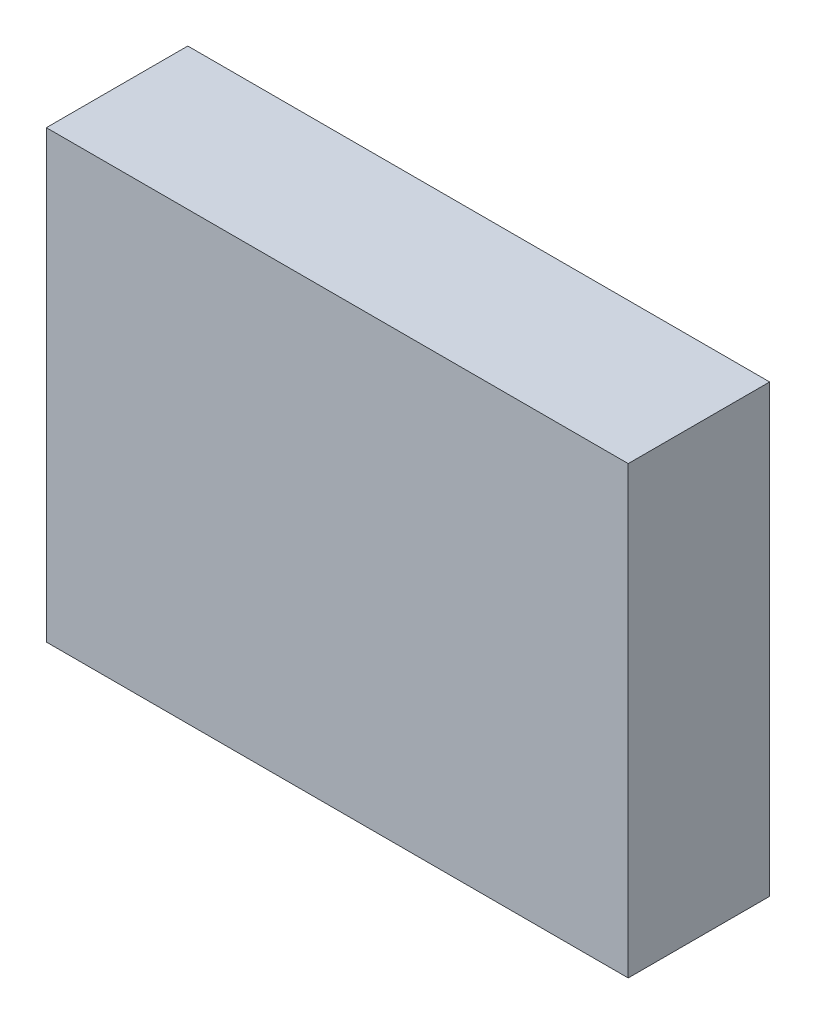
SolidWorks part; units mm, degrees
ref_plane "Alzado" through (0, 0, 0) normal (0, 0, 1) x (1, 0, 0)
ref_plane "Planta" through (0, 0, 0) normal (0, 1, 0) x (1, 0, 0)
ref_plane "Vista lateral" through (0, 0, 0) normal (1, 0, 0) x (0, 0, -1)
sketch "Croquis1" plane through (0, 0, 0) normal (0, 0, 1) x (1, 0, 0)
  line L1 (-56.96, -43.61) -> (56.96, -43.61)
  line L2 (-56.96, -43.61) -> (-56.96, 43.61)
  line L3 (-56.96, 43.61) -> (56.96, 43.61)
  line L4 (56.96, -43.61) -> (56.96, 43.61)
  line L5 (-56.96, -43.61) -> (56.96, 43.61) construction
  line L6 (-56.96, 43.61) -> (56.96, -43.61) construction
  point P0 (0, 0)
  dimension "D1" = 87.22
  dimension "D2" = 113.92
extrude "Saliente-Extruir3" add sketch "Croquis1" along normal blind 27.69 contours L2 L3 L4 L1
